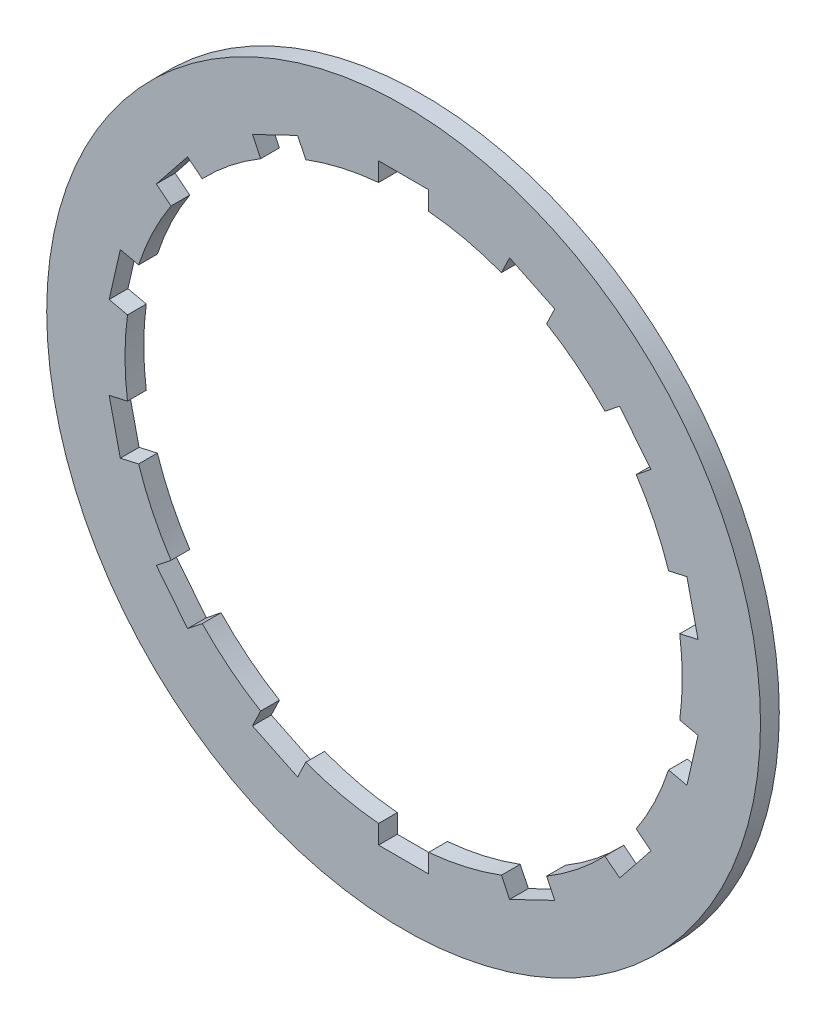
SolidWorks part; units mm, degrees
material "PETG"
ref_plane "Front Plane" through (0, 0, 0) normal (0, 0, 1) x (1, 0, 0)
ref_plane "Top Plane" through (0, 0, 0) normal (0, 1, 0) x (1, 0, 0)
ref_plane "Right Plane" through (0, 0, 0) normal (1, 0, 0) x (0, 0, -1)
sketch "Sketch1" plane through (0, 0, 0) normal (0, 0, 1) x (1, 0, 0)
  line L0 (0, 0) -> (0, 50000) construction
  circle A0 centre (0, 0) radius 57
  circle A1 centre (0, 0) radius 44.5
  dimension "D1" = 114
  dimension "D2" = 89
extrude "Boss-Extrude1" add sketch "Sketch1" along normal blind 3
sketch "Sketch3" plane through (0, 0, 3) normal (0, 0, 1) x (1, 0, 0)
  line L0 (-4, 47.3199) -> (4, 47.3199)
  line L2 (4, 47.3199) -> (4, 44.3199)
  line L3 (4, 44.3199) -> (-4, 44.3199)
  line L4 (-4, 44.3199) -> (-4, 47.3199)
  circle A0 centre (0, 0) radius 44.5 construction
  point P3 (0, 47.3199)
  dimension "D1" = 8
  dimension "D2" = 3
extrude "Cut-Extrude1" cut sketch "Sketch3" against normal up to next
pattern_circular "CirPattern1" count 14 over 360 about axis through (0, 0, 0) along (0, 0, 1) of "Cut-Extrude1"
equation "\"CanSat_Len\"= 400mm"
equation "\"CanSat_Dia\"= 150mm"
equation "\"BodyTube_ID\"= 114mm"
equation "\"BodyTube_OD\"= 120mm"
equation "\"PayLoadBay_ID\"= 164mm"
equation "\"PayLoadBay_OD\"= 170mm"
equation "\"ParachuteBay_Pitch\"= 400mm"
equation "\"ElectronicsTray_PitchDist\"= 50mm"
equation "\"ElectronicsTray_Height\"= 140mm"
equation "\"MotorDia\"= 98mm"
equation "\"MotorLen\"=289mm"
equation "\"D1@Sketch1\"=\"BodyTube_ID\""
